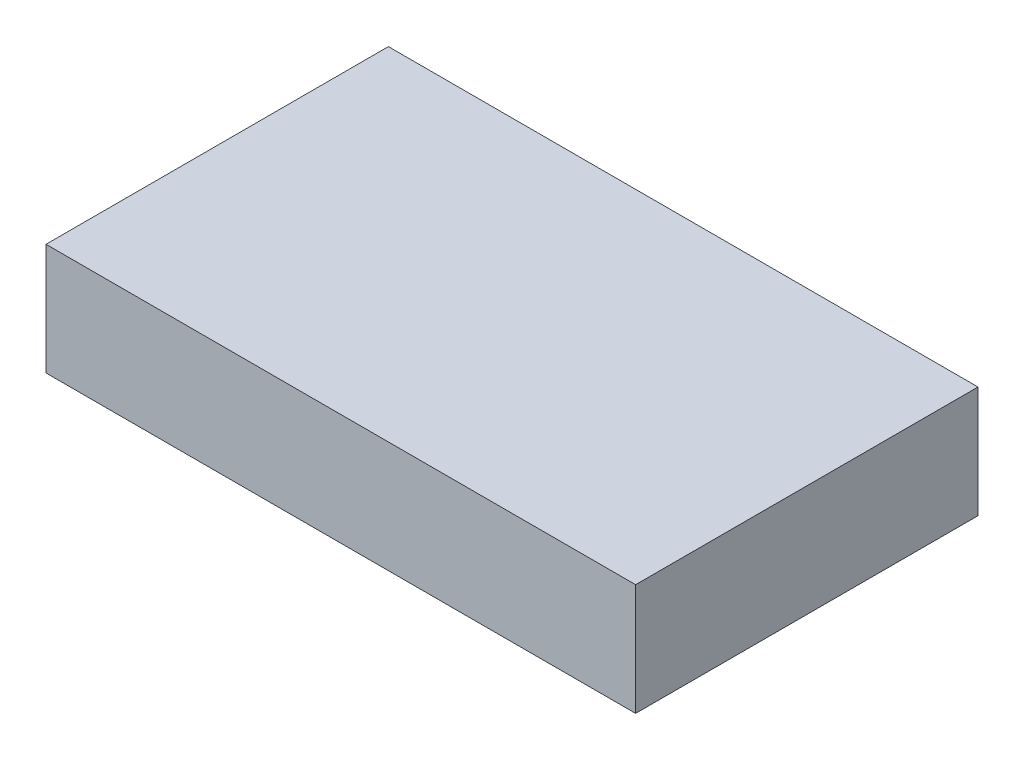
SolidWorks part; units mm, degrees
ref_plane "Front Plane" through (0, 0, 0) normal (0, 0, 1) x (1, 0, 0)
ref_plane "Top Plane" through (0, 0, 0) normal (0, 1, 0) x (1, 0, 0)
ref_plane "Right Plane" through (0, 0, 0) normal (1, 0, 0) x (0, 0, -1)
sketch "Sketch2" plane through (0, 0, 0) normal (0, 0, 1) x (1, 0, 0)
  line L0 (11.1072, -2.1) -> (-11.1072, -2.1)
  line L1 (-11.1072, -2.1) -> (-11.1072, 2.1)
  line L2 (-11.1072, 2.1) -> (11.1072, 2.1)
  line L3 (11.1072, 2.1) -> (11.1072, -2.1)
extrude "Boss-Extrude1" add sketch "Sketch2" along normal blind 12.9
